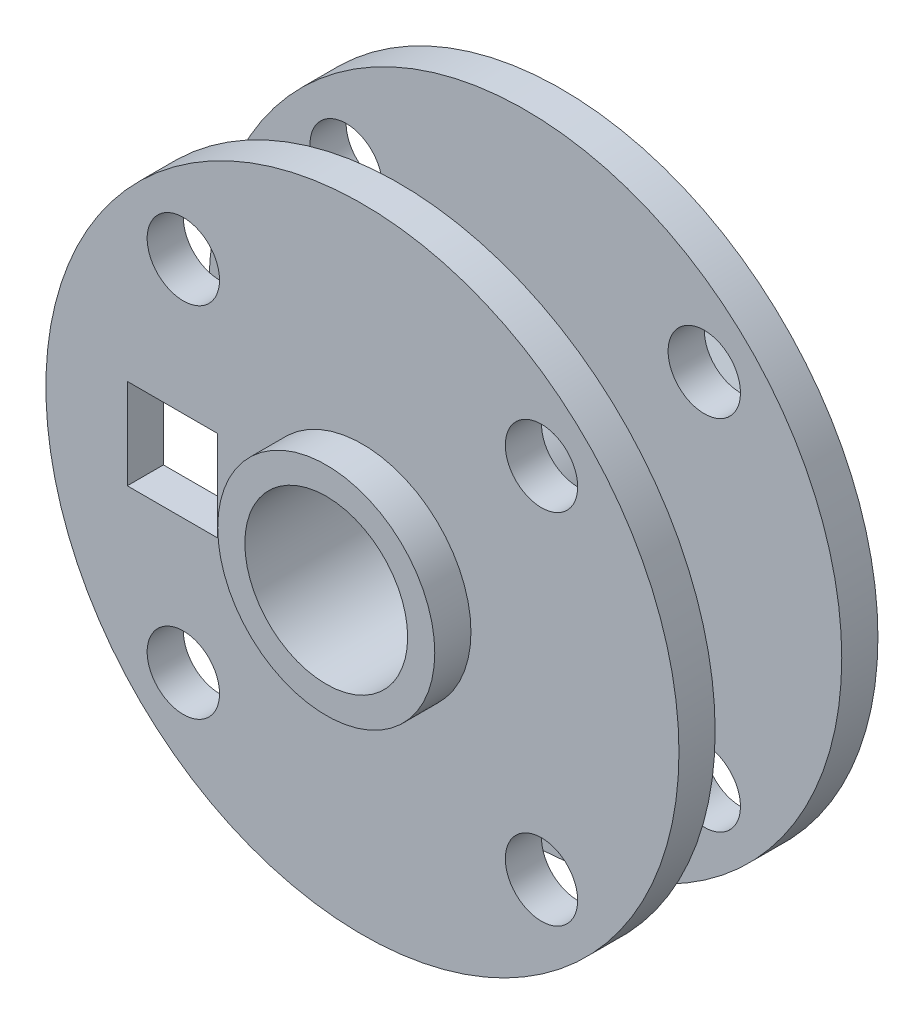
SolidWorks part; units mm, degrees
ref_plane "前视基准面" through (0, 0, 0) normal (0, 0, 1) x (1, 0, 0)
ref_plane "上视基准面" through (0, 0, 0) normal (0, 1, 0) x (1, 0, 0)
ref_plane "右视基准面" through (0, 0, 0) normal (1, 0, 0) x (0, 0, -1)
sketch "草图1" plane through (0, 0, 0) normal (0, 0, 1) x (1, 0, 0)
  circle A0 centre (0, 0) radius 17.5
  dimension "D1" = 35
extrude "凸台-拉伸1" add sketch "草图1" along normal blind 2
sketch "草图2" plane through (0, 0, 2) normal (0, 0, 1) x (1, 0, 0)
  circle A0 centre (0, 0) radius 7
  dimension "D1" = 14
extrude "凸台-拉伸2" add sketch "草图2" along normal blind 7
sketch "草图3" plane through (0, 0, 9) normal (0, 0, 1) x (1, 0, 0)
  circle A0 centre (0, 0) radius 17.5
  dimension "D1" = 35
extrude "凸台-拉伸3" add sketch "草图3" along normal blind 2
sketch "草图4" plane through (0, 0, 11) normal (0, 0, 1) x (1, 0, 0)
  line L1 (-13, 2.5) -> (-8, 2.5)
  line L2 (-13, 2.5) -> (-13, -2.5)
  line L3 (-13, -2.5) -> (-8, -2.5)
  line L4 (-8, 2.5) -> (-8, -2.5)
  dimension "D1" = 5
  dimension "D2" = 5
  dimension "D3" = 2.5
  dimension "D4" = 8
extrude "切除-拉伸1" cut sketch "草图4" against normal blind 18
sketch "草图5" plane through (0, 0, 0) normal (0, 0, -1) x (-1, 0, 0)
  circle A0 centre (0, 0) radius 4.5
  dimension "D1" = 9
extrude "切除-拉伸2" cut sketch "草图5" against normal blind 18
sketch "草图6" plane through (0, 0, 11) normal (0, 0, 1) x (1, 0, 0)
  circle A0 centre (0, 0) radius 6
  circle A1 centre (0, 0) radius 4.5
  dimension "D1" = 9
  dimension "D2" = 12
extrude "凸台-拉伸4" add sketch "草图6" along normal blind 2
sketch "草图7" plane through (0, 0, 11) normal (0, 0, 1) x (1, 0, 0)
  line L0 (-9.8995, 9.8995) -> (0, 0) construction
  line L1 (0, 17.5) -> (0, -17.5) construction
  circle A0 centre (0, 0) radius 14 construction
  circle A1 centre (-9.8995, 9.8995) radius 2
  circle A2 centre (0, 0) radius 17.5 construction
  circle A3 centre (9.8995, 9.8995) radius 2
  circle A4 centre (9.8995, -9.8995) radius 2
  circle A5 centre (-9.8995, -9.8995) radius 2
  point P19 (0, 0)
  dimension "D1" = 28
  dimension "D2" = 4
  dimension "D3" = 45
  dimension "D4" = 4
extrude "切除-拉伸3" cut sketch "草图7" against normal blind 20
sketch "草图8" plane through (0, 0, 0) normal (0, 0, -1) x (-1, 0, 0)
  circle A0 centre (0, 0) radius 6
  circle A1 centre (0, 0) radius 4.5
  dimension "D1" = 12
  dimension "D2" = 9
extrude "凸台-拉伸5" add sketch "草图8" along normal blind 2
sketch "草图10" plane through (0, 0, -2) normal (0, 0, -1) x (-1, 0, 0)
  line L1 (0, 8.0829) -> (-7, 4.0415)
  line L2 (-7, 4.0415) -> (-7, -4.0415)
  line L3 (-7, -4.0415) -> (0, -8.0829)
  line L4 (0, -8.0829) -> (7, -4.0415)
  line L5 (7, -4.0415) -> (7, 4.0415)
  line L6 (7, 4.0415) -> (0, 8.0829)
  circle A0 centre (0, 0) radius 7 construction
  circle A1 centre (0, 0) radius 4.5 construction
  circle A2 centre (0, 0) radius 4.5
  dimension "D1" = 14
extrude "凸台-拉伸6" add sketch "草图10" along normal blind 3
